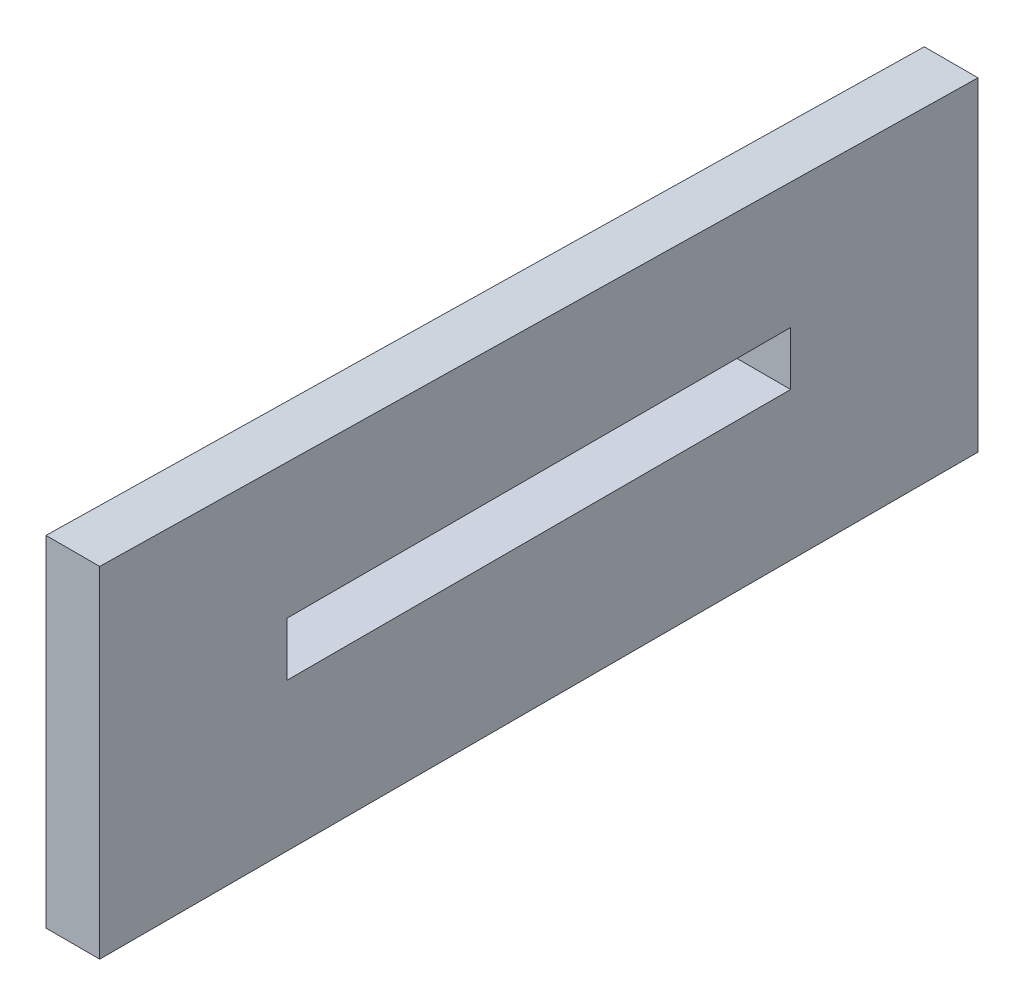
SolidWorks part; units mm, degrees
material "Birch Ply"
ref_plane "Front Plane" through (0, 0, 0) normal (0, 0, 1) x (1, 0, 0)
ref_plane "Top Plane" through (0, 0, 0) normal (0, 1, 0) x (1, 0, 0)
ref_plane "Right Plane" through (0, 0, 0) normal (1, 0, 0) x (0, 0, -1)
sketch "Sketch1" plane through (0, 0, 0) normal (1, 0, 0) x (0, 0, -1)
  line L0 (0, 9.5795) -> (0, -9.5795) construction
  line L1 (25.9539, 9.5795) -> (-25.9539, 10.5251)
  line L2 (-25.9539, 10.5251) -> (-25.9539, -9.5795)
  line L3 (-25.9539, -9.5795) -> (25.9539, -9.5795)
  line L4 (25.9539, 9.5795) -> (25.9539, -9.5795)
  line L5 (-25.9539, 0) -> (25.9539, 0) construction
  line L7 (-14.8811, 2.3386) -> (14.8811, 2.3386)
  line L8 (-14.8811, 2.3386) -> (-14.8811, -0.8364)
  line L9 (-14.8811, -0.8364) -> (14.8811, -0.8364)
  line L10 (14.8811, 2.3386) -> (14.8811, -0.8364)
  dimension "D1" = 11.0727
  dimension "D2" = 19.1589
  dimension "D3" = 20.1045
  dimension "D4" = 3.175
  dimension "D5" = 29.7622
  dimension "D6" = 11.0727
  dimension "D7" = 8.7431
extrude "Boss-Extrude1" add sketch "Sketch1" along normal blind 3.175
